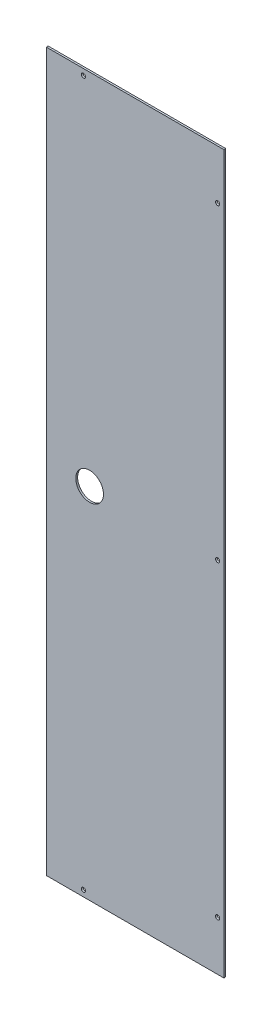
SolidWorks part; units mm, degrees
other "Top Cover Panel 1"
ref_plane "Front Plane" through (0, 0, 0) normal (0, 0, 1) x (1, 0, 0)
ref_plane "Top Plane" through (0, 0, 0) normal (0, 1, 0) x (1, 0, 0)
ref_plane "Right Plane" through (0, 0, 0) normal (1, 0, 0) x (0, 0, -1)
sketch3d "Main Profile Sketch datum points"
  point P0 (0, 0, 111.5)
  point P1 (10, 0, 111.5)
  point P2 (0, 10, 111.5)
ref_plane "Main Profile Sketch plane" through (0, 0, 111.5) normal (0, 0, 1) x (1, 0, 0)
sketch "Main Profile Sketch" plane through (0, 0, 111.5) normal (0, 0, 1) x (1, 0, 0)
  line L0 (-285, 290) -> (-141.5, 290)
  line L1 (-141.5, 290) -> (-141.5, -290)
  line L2 (-285, -290) -> (-141.5, -290)
  line L3 (-285, 290) -> (-285, -290)
  circle A0 centre (-255, -285) radius 1.7
  circle A1 centre (-146.5, -250) radius 1.7
  circle A2 centre (-250, 0) radius 11.2
  circle A3 centre (-255, 285) radius 1.7
  circle A4 centre (-146.5, 0) radius 1.7
  circle A5 centre (-146.5, 250) radius 1.7
extrude "Main Extrusion" add sketch "Main Profile Sketch" against normal blind 1.5 separate body
